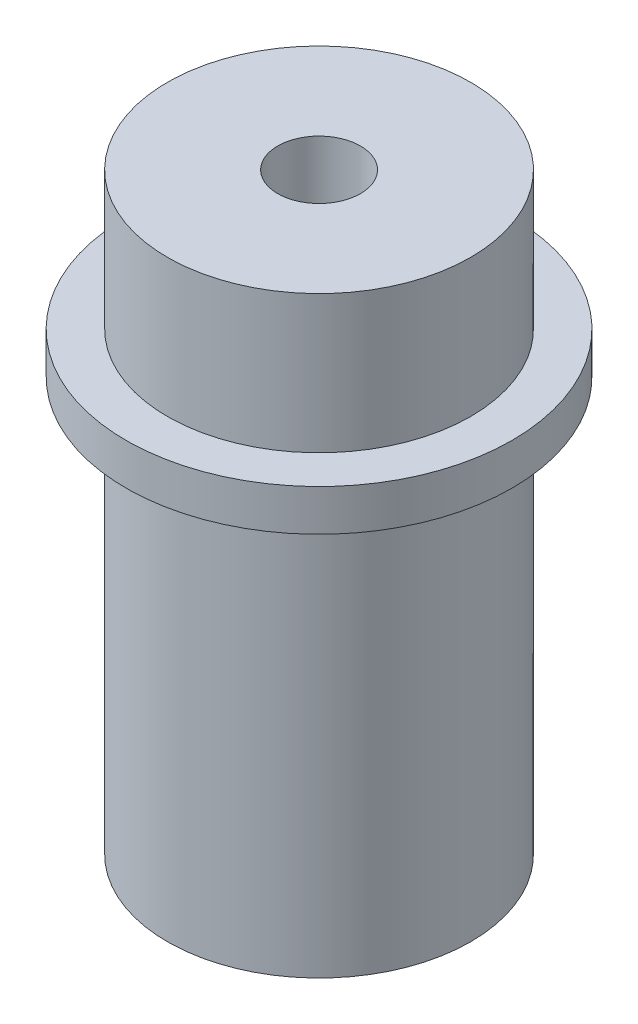
SolidWorks part; units mm, degrees
ref_plane "Front Plane" through (0, 0, 0) normal (0, 0, 1) x (1, 0, 0)
ref_plane "Top Plane" through (0, 0, 0) normal (0, 1, 0) x (1, 0, 0)
ref_plane "Right Plane" through (0, 0, 0) normal (1, 0, 0) x (0, 0, -1)
sketch "Sketch1" plane through (0, 0, 0) normal (0, 0, 1) x (1, 0, 0)
  line L2 (0, 0) -> (-11, 0)
  line L3 (0, 0) -> (0, 30)
  line L4 (0, 30) -> (-11, 30)
  line L5 (-11, 0) -> (-11, 30)
  line L6 (0, 30) -> (-14, 30)
  line L7 (0, 30) -> (0, 33)
  line L8 (0, 33) -> (-14, 33)
  line L9 (-14, 30) -> (-14, 33)
  line L10 (0, 33) -> (-11, 33)
  line L11 (0, 33) -> (0, 43)
  line L12 (0, 43) -> (-11, 43)
  line L13 (-11, 33) -> (-11, 43)
  line L14 (0, 43) -> (-3, 43)
  line L15 (0, 43) -> (0, 0)
  line L16 (0, 0) -> (-3, 0)
  line L17 (-3, 43) -> (-3, 0)
  point P14 (-14, 10.8346)
  point P15 (0, 5.94)
  point P16 (0, -17.1046)
  dimension "D1" = 11
  dimension "D2" = 3
  dimension "D3" = 10
  dimension "D4" = 3
  dimension "D5" = 3
  dimension "D6" = 30
revolve "Revolve1" add sketch "Sketch1" angle 360 about L3
